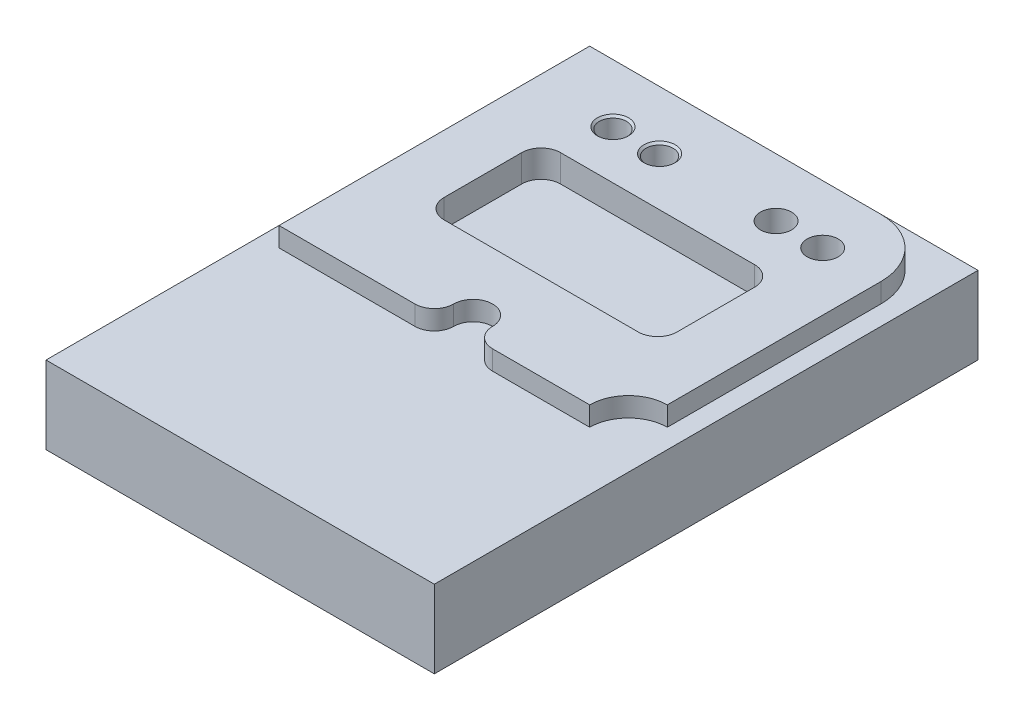
SolidWorks part; units mm, degrees
ref_plane "Front Plane" through (0, 0, 0) normal (0, 0, 1) x (1, 0, 0)
ref_plane "Top Plane" through (0, 0, 0) normal (0, 1, 0) x (1, 0, 0)
ref_plane "Right Plane" through (0, 0, 0) normal (1, 0, 0) x (0, 0, -1)
sketch "Sketch1" plane through (0, 0, 0) normal (0, 1, 0) x (1, 0, 0)
  line L1 (-237.4096, 148.2229) -> (-137.4096, 148.2229)
  line L2 (-237.4096, 148.2229) -> (-237.4096, 8.2229)
  line L3 (-237.4096, 8.2229) -> (-137.4096, 8.2229)
  line L4 (-137.4096, 148.2229) -> (-137.4096, 8.2229)
  line L5 (-237.4096, 148.2229) -> (-137.4096, 8.2229) construction
  line L6 (-237.4096, 8.2229) -> (-137.4096, 148.2229) construction
  point P0 (-187.4096, 78.2229)
  dimension "D1" = 140
  dimension "D2" = 100
  dimension "D3" = 140
  dimension "D4" = 100
extrude "Boss-Extrude1" add sketch "Sketch1" along normal blind 25
sketch "Sketch2" plane through (0, 25, 0) normal (0, 1, 0) x (1, 0, 0)
  line L0 (-237.4096, 8.2229) -> (-237.4096, 63.2229)
  line L1 (-237.4096, 148.2229) -> (-237.4096, 8.2229) construction
  line L2 (-237.4096, 63.2229) -> (-137.4096, 63.2229)
  line L3 (-137.4096, 8.2229) -> (-137.4096, 148.2229) construction
  line L4 (-137.4096, 63.2229) -> (-137.4096, 8.2229)
  line L5 (-137.4096, 8.2229) -> (-237.4096, 8.2229)
  dimension "D1" = 55
extrude "Cut-Extrude1" cut sketch "Sketch2" against normal blind 5
sketch "Sketch3" plane through (0, 25, 0) normal (0, 1, 0) x (1, 0, 0)
  line L0 (-237.4096, 63.2229) -> (-232.4096, 63.2229)
  line L1 (-137.4096, 63.2229) -> (-237.4096, 63.2229) construction
  line L2 (-232.4096, 63.2229) -> (-232.4096, 143.2229)
  line L3 (-232.4096, 143.2229) -> (-157.4096, 143.2229)
  line L5 (-137.4096, 63.2229) -> (-237.4096, 63.2229) construction
  line L6 (-232.4096, 63.2229) -> (-197.4096, 63.2229)
  line L7 (-142.4096, 73.2229) -> (-142.4096, 128.2229)
  line L8 (-232.4096, 63.2229) -> (-197.4096, 63.2229)
  line L9 (-232.4096, 63.2229) -> (-197.4096, 63.2229)
  line L10 (-237.4096, 63.2229) -> (-237.4096, 148.2229)
  line L11 (-237.4096, 148.2229) -> (-137.4096, 148.2229)
  line L12 (-137.4096, 148.2229) -> (-137.4096, 63.2229)
  line L13 (-137.4096, 63.2229) -> (-152.4096, 63.2229)
  line L14 (-172.4096, 63.2229) -> (-152.4096, 63.2229)
  line L15 (-197.4096, 63.2229) -> (-177.4096, 63.2229)
  line L18 (-177.4096, 63.2229) -> (-172.4096, 63.2229)
  arc A0 (-142.4096, 128.2229) -> (-157.4096, 143.2229) centre (-157.4096, 128.2229) ccw
  arc A1 (-142.4096, 73.2229) -> (-152.4096, 63.2229) centre (-142.4096, 63.2229) ccw
  arc A5 (-197.4096, 63.2229) -> (-192.4096, 68.2229) centre (-197.4096, 68.2229) ccw
  arc A6 (-182.4096, 68.2229) -> (-192.4096, 68.2229) centre (-187.4096, 68.2229) ccw
  arc A7 (-182.4096, 68.2229) -> (-177.4096, 63.2229) centre (-177.4096, 68.2229) ccw
  point P12 (-142.4096, 143.2229)
  line M19 (-237.4096, 63.2229) -> (-137.4096, 63.2229)
  line M20 (-137.4096, 63.2229) -> (-137.4096, 148.2229)
  line M21 (-137.4096, 148.2229) -> (-237.4096, 148.2229)
  line M22 (-237.4096, 148.2229) -> (-237.4096, 63.2229)
  dimension "D5" = 15
  dimension "D7" = 5
  dimension "D6" = 10
  dimension "D9" = 5
  dimension "D8" = 5
  dimension "D1" = 5
  dimension "D2" = 80
  dimension "D3" = 90
  dimension "D4" = 80
  dimension "D10" = 20
  dimension "D11" = 35
  dimension "D12" = 5
extrude "Cut-Extrude2" cut sketch "Sketch3" against normal blind 5 contours L7 A1 L2 L3 A0 M19 M20 M21 M22 | A7 A6 A5 M19
sketch "Sketch5" plane through (0, 25, 0) normal (0, 1, 0) x (1, 0, 0)
  line L0 (-237.4096, 8.2229) -> (-237.4096, 128.2229)
  line L1 (-237.4096, 148.2229) -> (-237.4096, 8.2229) construction
  line L2 (-237.4096, 128.2229) -> (-214.4096, 128.2229)
  line L3 (-214.4096, 128.2229) -> (-199.4096, 128.2229)
  line L4 (-199.4096, 128.2229) -> (-169.4096, 128.2229)
  line L5 (-169.4096, 128.2229) -> (-157.4096, 128.2229)
  circle A0 centre (-214.4096, 128.2229) radius 4
  circle A1 centre (-199.4096, 128.2229) radius 4
  circle A2 centre (-169.4096, 128.2229) radius 4
  circle A3 centre (-157.4096, 128.2229) radius 4
  dimension "D6" = 8
  dimension "D7" = 8
  dimension "D8" = 8
  dimension "D9" = 8
  dimension "D1" = 120
  dimension "D2" = 23
  dimension "D3" = 15
  dimension "D4" = 30
  dimension "D5" = 12
extrude "Cut-Extrude3" cut sketch "Sketch5" against normal blind 10 contours L4 A2 L5 | L5 A2 L4 | A3
sketch "Sketch7" plane through (0, 25, 0) normal (0, 1, 0) x (1, 0, 0)
  circle A0 centre (-211.4096, 128.2229) radius 4
  circle A1 centre (-199.4096, 128.2229) radius 4
  dimension "D3" = 8
  dimension "D4" = 8
  dimension "D2" = 12
hole_wizard "M8x1.0 Tapped Hole1" positions "3DSketch2" profile "Sketch12" tap size "M8x1.0" standard "ANSI Metric"
sketch3d "3DSketch2"
  point P0 (-211.4096, 25, -128.2229)
  point P3 (-199.4096, 25, -128.2229)
sketch "Sketch12" plane through (-211.4096, 25, -128.2229) normal (1, 0, 0) x (0, 0, 1)
  line L0 (0, 0) -> (0, 15)
  line L1 (0, 15) -> (3.5, 12.897)
  line L2 (3.5, 12.897) -> (3.5, 0.525)
  line L3 (3.5, 0.525) -> (4.025, 0)
  line L5 (4.025, 0) -> (0, 0)
  line L6 (-3.5, 0.525) -> (-4.025, 0) construction
  line L10 (0, 15) -> (-3.5, 12.897) construction
  line L11 (0, -6.35) -> (0, 107.95) construction
  dimension "Tap Drill Dia." = 7
  dimension "Tap Drill Depth" = 15
  dimension "Near C'Sink Dia." = 8.05
  dimension "Near C'Sink Angle" = 90
  dimension "Drill Angle" = 118
sketch "Sketch13" plane through (0, 25, 0) normal (0, 1, 0) x (1, 0, 0)
  line L0 (-237.4096, 8.2229) -> (-237.4096, 100.7229)
  line L1 (-237.4096, 148.2229) -> (-237.4096, 8.2229) construction
  line L2 (-237.4096, 100.7229) -> (-187.4096, 100.7229)
  line L4 (-162.4096, 85.7229) -> (-212.4096, 85.7229)
  line L5 (-157.4096, 90.7229) -> (-157.4096, 110.7229)
  line L6 (-162.4096, 115.7229) -> (-212.4096, 115.7229)
  line L7 (-217.4096, 90.7229) -> (-217.4096, 110.7229)
  line L8 (-157.4096, 85.7229) -> (-217.4096, 115.7229) construction
  line L9 (-157.4096, 115.7229) -> (-217.4096, 85.7229) construction
  arc A0 (-157.4096, 110.7229) -> (-162.4096, 115.7229) centre (-162.4096, 110.7229) ccw
  arc A1 (-157.4096, 90.7229) -> (-162.4096, 85.7229) centre (-162.4096, 90.7229) cw
  arc A2 (-217.4096, 90.7229) -> (-212.4096, 85.7229) centre (-212.4096, 90.7229) ccw
  arc A3 (-212.4096, 115.7229) -> (-217.4096, 110.7229) centre (-212.4096, 110.7229) ccw
  dimension "D5" = 5
  dimension "D1" = 92.5
  dimension "D2" = 50
  dimension "D3" = 30
  dimension "D4" = 60
extrude "Cut-Extrude4" cut sketch "Sketch13" against normal blind 7
